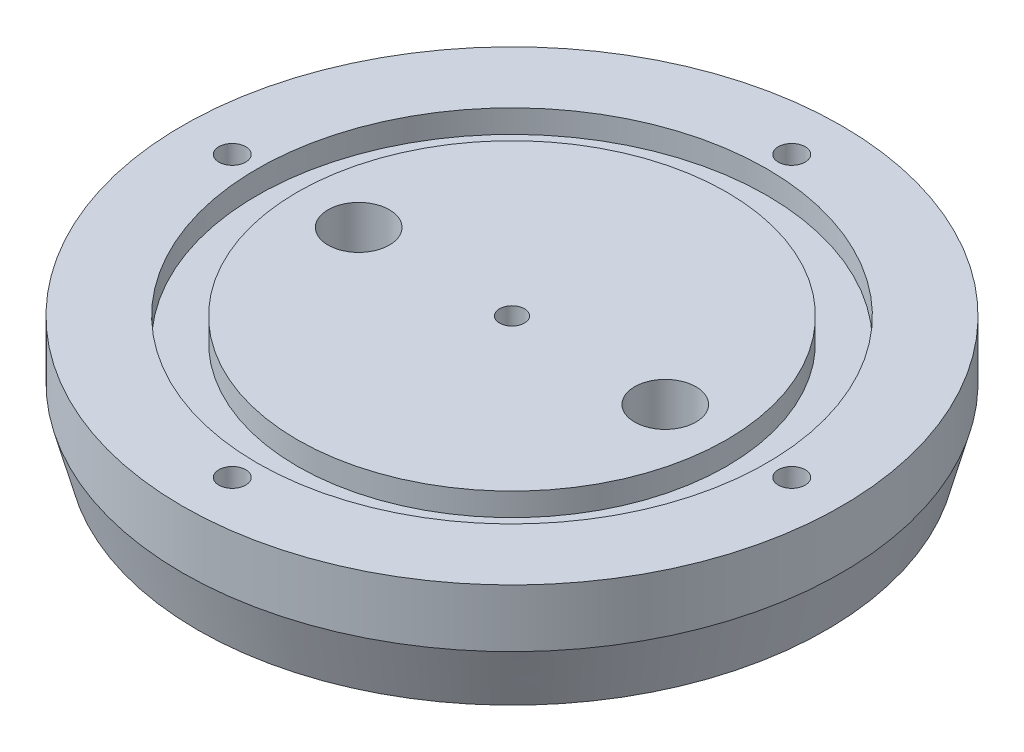
SolidWorks part; units mm, degrees
ref_plane "Front Plane" through (0, 0, 0) normal (0, 0, 1) x (1, 0, 0)
ref_plane "Top Plane" through (0, 0, 0) normal (0, 1, 0) x (1, 0, 0)
ref_plane "Right Plane" through (0, 0, 0) normal (1, 0, 0) x (0, 0, -1)
sketch "Sketch1" plane through (0, 0, 0) normal (0, 1, 0) x (1, 0, 0)
  circle A0 centre (0, 0) radius 43
  dimension "D1" = 86
extrude "Boss-Extrude1" add sketch "Sketch1" along normal blind 15
sketch "Sketch2" plane through (0, 0, 0) normal (0, -1, 0) x (1, 0, 0)
  circle A0 centre (20, 0) radius 4
  circle A1 centre (-20, 0) radius 4
  dimension "D1" = 8
  dimension "D2" = 8
  dimension "D3" = 20
  dimension "D4" = 20
extrude "Cut-Extrude1" cut sketch "Sketch2" against normal through all
sketch "Sketch3" plane through (0, 15, 0) normal (0, 1, 0) x (1, 0, 0)
  circle A0 centre (0, 0) radius 1.625
  dimension "D1" = 3.25
extrude "Cut-Extrude2" cut sketch "Sketch3" against normal through all
sketch "Sketch4" plane through (0, 15, 0) normal (0, 1, 0) x (1, 0, 0)
  circle A0 centre (0, 0) radius 28
  circle A1 centre (0, 0) radius 33.25
  dimension "D1" = 56
  dimension "D2" = 66.5
extrude "Cut-Extrude3" cut sketch "Sketch4" against normal blind 3
sketch "Sketch5" plane through (0, 0, 0) normal (0, -1, 0) x (1, 0, 0)
  circle A0 centre (36.5, 0) radius 1.75
  dimension "D1" = 36.5
  dimension "D2" = 3.5
extrude "Cut-Extrude4" cut sketch "Sketch5" against normal through all
pattern_circular "CirPattern1" count 4 over 360 about axis through (0, 0, 0) along (0, 1, 0) of "Cut-Extrude4"
chamfer "Chamfer1" distance 2 angle 75 1 edges at (0, 0, 43)
chamfer "Chamfer2" distance 0.5 angle 45 3 edges at (20, 0, -4) (0, 0, 1.625) (-20, 0, -4)
